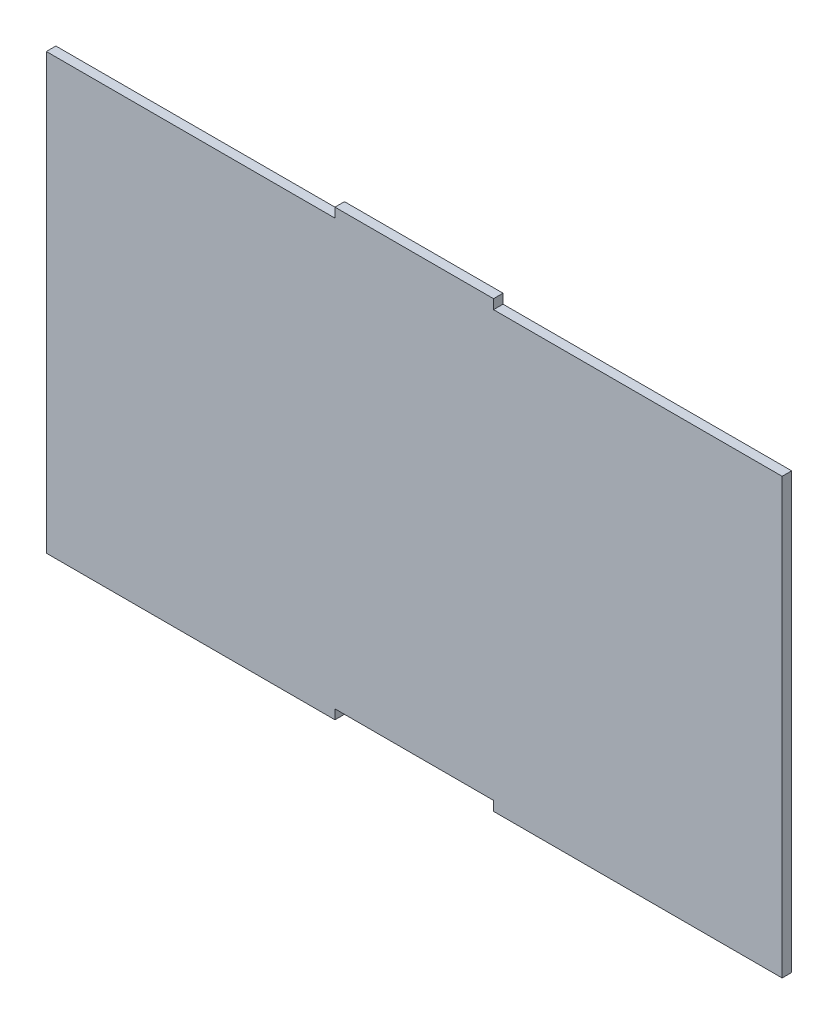
SolidWorks part; units mm, degrees
material "Teca"
ref_plane "Plano frontal" through (0, 0, 0) normal (0, 0, 1) x (1, 0, 0)
ref_plane "Plano superior" through (0, 0, 0) normal (0, 1, 0) x (1, 0, 0)
ref_plane "Plano direito" through (0, 0, 0) normal (1, 0, 0) x (0, 0, -1)
sketch "Esboço1" plane through (0, 0, 0) normal (0, 0, 1) x (1, 0, 0)
  line L0 (0, 0) -> (0, 137)
  line L1 (0, 137) -> (91, 137)
  line L2 (91, 137) -> (91, 140)
  line L3 (91, 140) -> (141, 140)
  line L4 (141, 140) -> (141, 137)
  line L5 (141, 137) -> (232, 137)
  line L6 (232, 137) -> (232, 0)
  line L7 (232, 0) -> (141, 0)
  line L8 (141, 0) -> (141, 3)
  line L9 (141, 3) -> (91, 3)
  line L10 (91, 3) -> (91, 0)
  line L11 (91, 0) -> (0, 0)
  dimension "D1" = 137
  dimension "D2" = 3
  dimension "D3" = 50
  dimension "D4" = 91
  dimension "D5" = 91
  dimension "D6" = 3
  dimension "D7" = 50
  dimension "D8" = 3
  dimension "91" = 91
extrude "Ressalto-extrusão1" add sketch "Esboço1" along normal blind 3
